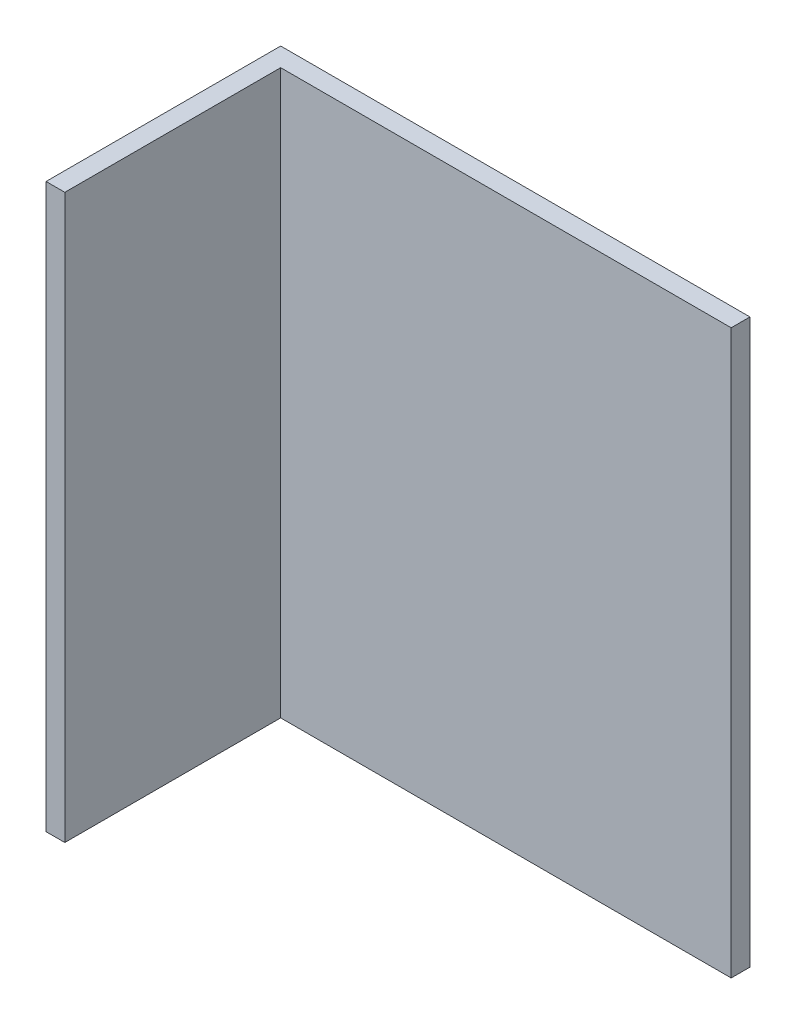
SolidWorks part; units mm, degrees
ref_plane "前视" through (0, 0, 0) normal (0, 0, 1) x (1, 0, 0)
ref_plane "上视" through (0, 0, 0) normal (0, 1, 0) x (1, 0, 0)
ref_plane "右视" through (0, 0, 0) normal (1, 0, 0) x (0, 0, -1)
sketch "草图1" plane through (0, 0, 0) normal (0, 0, 1) x (1, 0, 0)
  line L0 (160, 281.9635) -> (160, -120.4694) construction
  line L1 (0, 0) -> (200, 0)
  line L2 (0, 0) -> (0, 240)
  line L3 (0, 240) -> (200, 240)
  line L4 (200, 0) -> (200, 240)
  dimension "D1" = 240
  dimension "D2" = 200
  dimension "D3" = 160
extrude "基体-拉伸" add sketch "草图1" along normal blind 8
sketch "草图2" plane through (0, 0, 8) normal (0, 0, 1) x (1, 0, 0)
  line L1 (0, 240) -> (8, 240)
  line L2 (0, 240) -> (0, 0)
  line L3 (0, 0) -> (8, 0)
  line L4 (8, 240) -> (8, 0)
  dimension "D1" = 8
extrude "凸台-拉伸1" add sketch "草图2" along normal blind 92
